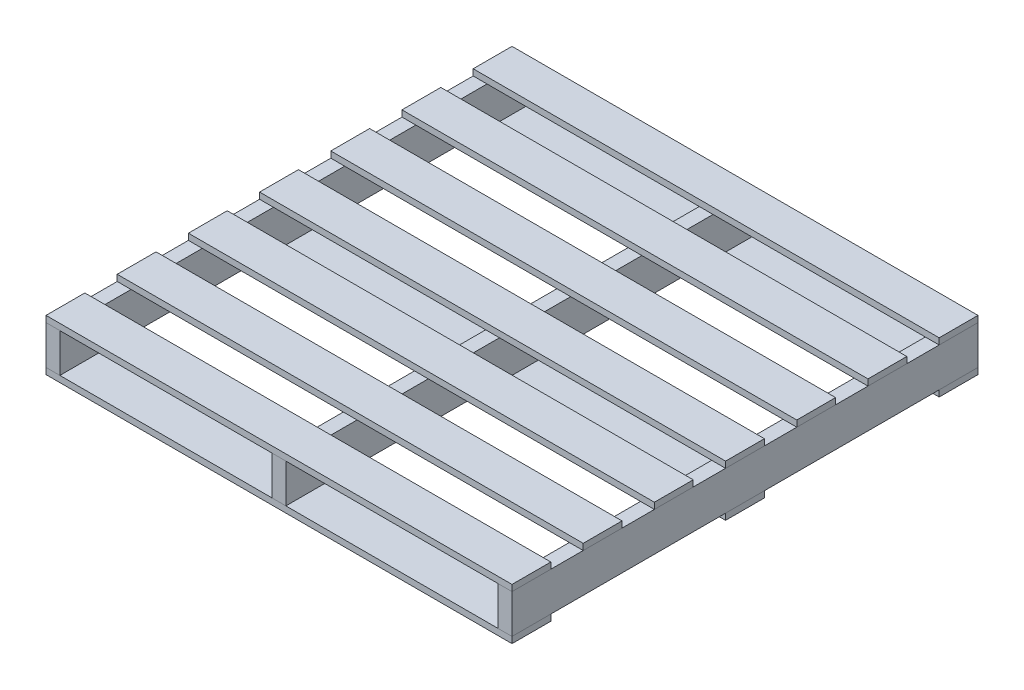
SolidWorks part; units mm, degrees
ref_plane "Front Plane" through (0, 0, 0) normal (0, 0, 1) x (1, 0, 0)
ref_plane "Top Plane" through (0, 0, 0) normal (0, 1, 0) x (1, 0, 0)
ref_plane "Right Plane" through (0, 0, 0) normal (1, 0, 0) x (0, 0, -1)
sketch "Sketch1" plane through (0, 0, 0) normal (0, 0, 1) x (1, 0, 0)
  line L0 (-533.4, 0) -> (533.4, 0) construction
  line L5 (-533.4, 58.7502) -> (-533.4, -58.7502) construction
  line L6 (533.4, 58.7502) -> (533.4, -58.7502) construction
  line L11 (-533.4, -58.7502) -> (533.4, -58.7502) construction
  line L12 (-533.4, 58.7502) -> (533.4, 58.7502) construction
  line L13 (-501.65, 58.7502) -> (-501.65, -58.7502) construction
  line L14 (501.65, 58.7502) -> (501.65, -58.7502) construction
  line L15 (-15.748, 58.7502) -> (-15.748, -58.7502) construction
  line L16 (15.748, -58.7502) -> (15.748, 58.7502) construction
  line L17 (0, 58.7502) -> (0, -58.7502) construction
  line L18 (-533.4, 0) -> (-501.65, 0)
  line L19 (-15.748, 0) -> (0, 0)
  line L20 (0, 0) -> (15.748, 0)
  line L21 (501.65, 0) -> (533.4, 0)
  line L22 (-533.4, 44.45) -> (533.4, 44.45) construction
  line L23 (-533.4, -44.45) -> (533.4, -44.45) construction
  point P3 (0, 0)
  point P6 (-533.4, 0)
  point P9 (533.4, 0)
  point P23 (0, 0)
  dimension "Overall Width" = 1066.8
  dimension "Overall Height" = 117.5004
  dimension "Maximum Fork Width" = 485.902
  dimension "D2" = 485.902
  dimension "Maximum Fork Height" = 88.9
  dimension "D1" = 31.75
  dimension "D3" = 14.3002
sketch "Sketch2" plane through (0, 0, 0) normal (1, 0, 0) x (0, 0, -1)
  line L0 (533.4, 0) -> (-533.4, 0) construction
  point P4 (0, 0)
  dimension "Overall Depth" = 1066.8
sketch "Sketch3" plane through (0, 0, 0) normal (0, 0, 1) x (1, 0, 0)
  line L0 (-501.65, 58.7502) -> (-501.65, -58.7502) construction
  line L1 (-533.4, 44.45) -> (-501.65, 44.45)
  line L2 (-533.4, 44.45) -> (-533.4, -44.45)
  line L3 (-533.4, -44.45) -> (-501.65, -44.45)
  line L4 (-501.65, 44.45) -> (-501.65, -44.45)
  line L5 (-533.4, -44.45) -> (533.4, -44.45) construction
  line L6 (-15.748, 58.7502) -> (-15.748, -58.7502) construction
  line L7 (-15.748, 44.45) -> (15.748, 44.45)
  line L8 (-15.748, 44.45) -> (-15.748, -44.45)
  line L9 (-15.748, -44.45) -> (15.748, -44.45)
  line L10 (15.748, 44.45) -> (15.748, -44.45)
  line L11 (-533.4, 44.45) -> (533.4, 44.45) construction
  line L12 (15.748, -58.7502) -> (15.748, 58.7502) construction
  line L13 (501.65, 58.7502) -> (501.65, -58.7502) construction
  line L14 (501.65, 44.45) -> (533.4, 44.45)
  line L15 (501.65, 44.45) -> (501.65, -44.45)
  line L16 (501.65, -44.45) -> (533.4, -44.45)
  line L17 (533.4, 44.45) -> (533.4, -44.45)
extrude "Boss-Extrude1" add sketch "Sketch3" along normal up to vertex (533.4 mm away) and the other way up to vertex (533.4 mm away) up to point (0, 0, 533.4) other way up to point (0, 0, -533.4)
sketch "Sketch4" plane through (0, 44.45, 0) normal (0, 1, 0) x (1, 0, 0)
  line L0 (533.4, -533.4) -> (533.4, 533.4) construction
  line L1 (-533.4, -533.4) -> (533.4, -533.4)
  line L2 (-533.4, -533.4) -> (-533.4, -444.5)
  line L3 (-533.4, -444.5) -> (533.4, -444.5)
  line L4 (533.4, -533.4) -> (533.4, -444.5)
  line L5 (-533.4, -370.4167) -> (533.4, -370.4167)
  line L6 (-533.4, -370.4167) -> (-533.4, -281.5167)
  line L7 (-533.4, -281.5167) -> (533.4, -281.5167)
  line L8 (533.4, -370.4167) -> (533.4, -281.5167)
  line L9 (-533.4, -207.4333) -> (533.4, -207.4333)
  line L10 (-533.4, -207.4333) -> (-533.4, -118.5333)
  line L11 (-533.4, -118.5333) -> (533.4, -118.5333)
  line L12 (533.4, -207.4333) -> (533.4, -118.5333)
  line L13 (-533.4, -44.45) -> (533.4, -44.45)
  line L14 (-533.4, -44.45) -> (-533.4, 44.45)
  line L15 (-533.4, 44.45) -> (533.4, 44.45)
  line L16 (533.4, -44.45) -> (533.4, 44.45)
  line L17 (-533.4, 118.5333) -> (533.4, 118.5333)
  line L18 (-533.4, 118.5333) -> (-533.4, 207.4333)
  line L19 (-533.4, 207.4333) -> (533.4, 207.4333)
  line L20 (533.4, 118.5333) -> (533.4, 207.4333)
  line L21 (-533.4, -533.4) -> (-533.4, 533.4) construction
  line L22 (-533.4, 281.5167) -> (533.4, 281.5167)
  line L23 (-533.4, 281.5167) -> (-533.4, 370.4167)
  line L24 (-533.4, 370.4167) -> (533.4, 370.4167)
  line L25 (533.4, 281.5167) -> (533.4, 370.4167)
  line L26 (-533.4, 444.5) -> (533.4, 444.5)
  line L27 (-533.4, 444.5) -> (-533.4, 533.4)
  line L28 (-533.4, 533.4) -> (533.4, 533.4)
  line L29 (533.4, 444.5) -> (533.4, 533.4)
  dimension "D1" = 88.9
  dimension "D3" = 74.0833
  dimension "Top Boards" = 7
extrude "Boss-Extrude2" add sketch "Sketch4" along normal up to vertex (14.3002 mm away) separate body up to point (-533.4, 58.7502, 0)
sketch "Sketch5" plane through (0, -44.45, 0) normal (0, -1, 0) x (1, 0, 0)
  line L0 (533.4, 533.4) -> (533.4, -533.4) construction
  line L1 (-533.4, 533.4) -> (533.4, 533.4)
  line L2 (-533.4, 533.4) -> (-533.4, 444.5)
  line L3 (-533.4, 444.5) -> (533.4, 444.5)
  line L4 (533.4, 533.4) -> (533.4, 444.5)
  line L5 (-533.4, -533.4) -> (533.4, -533.4)
  line L6 (-533.4, -533.4) -> (-533.4, -444.5)
  line L7 (-533.4, -444.5) -> (533.4, -444.5)
  line L8 (533.4, -533.4) -> (533.4, -444.5)
  line L9 (-533.4, -44.45) -> (533.4, -44.45)
  line L10 (-533.4, -44.45) -> (-533.4, 44.45)
  line L11 (-533.4, 44.45) -> (533.4, 44.45)
  line L12 (533.4, -44.45) -> (533.4, 44.45)
  line L13 (-533.4, -44.45) -> (533.4, 44.45) construction
  line L14 (-533.4, 44.45) -> (533.4, -44.45) construction
  line L16 (-533.4, 533.4) -> (-533.4, 444.5) construction
  line L17 (533.4, 533.4) -> (533.4, 444.5) construction
  point P12 (0, 0)
extrude "Boss-Extrude3" add sketch "Sketch5" along normal up to vertex (14.3002 mm away) separate body up to point (-533.4, -58.7502, 0)
sketch "Sketch7" plane through (0, 0, 0) normal (0, 1, 0) x (1, 0, 0)
  line L0 (0, 533.4) -> (533.4, 533.4) construction
  line L2 (533.4, 533.4) -> (533.4, 0) construction
  line L3 (533.4, 0) -> (533.4, -533.4) construction
  line L4 (533.4, -533.4) -> (0, -533.4) construction
  line L5 (-533.4, -533.4) -> (533.4, -533.4) construction
  line L6 (-533.4, 533.4) -> (0, 533.4) construction
equation "\"D2@Sketch1\" = \"Maximum Fork Width@Sketch1\""
equation "\"D3@Sketch4\" =  ( \"Overall Depth@Sketch2\" -  ( 3.5 * \"Top Boards@Sketch4\" )  )  /  ( \"Top Boards@Sketch4\" - 1 ) "
